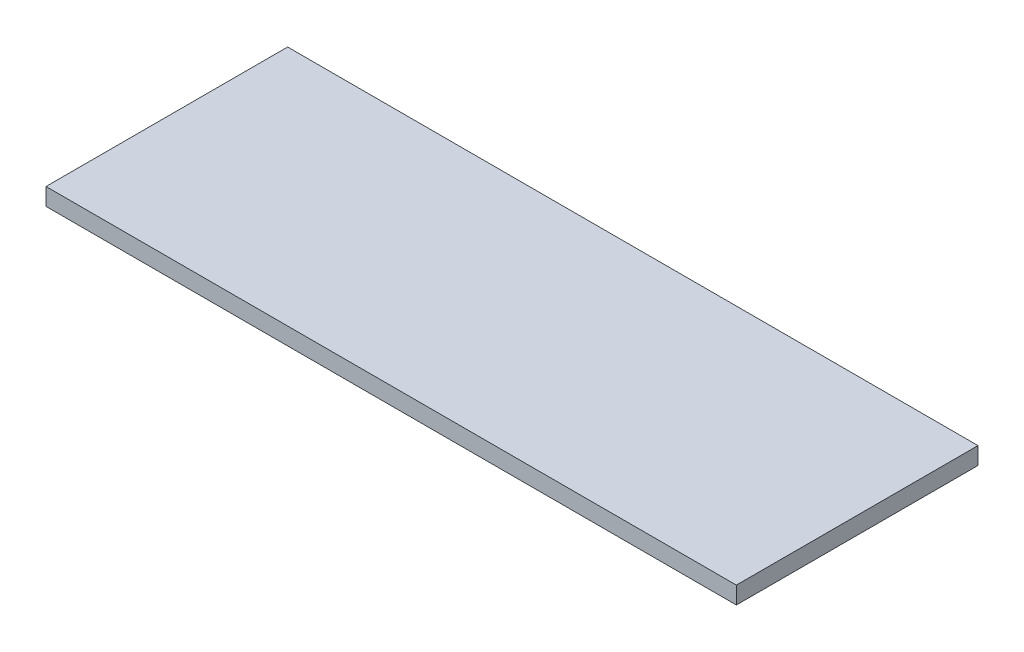
SolidWorks part; units mm, degrees
ref_plane "Front Plane" through (0, 0, 0) normal (0, 0, 1) x (1, 0, 0)
ref_plane "Top Plane" through (0, 0, 0) normal (0, 1, 0) x (1, 0, 0)
ref_plane "Right Plane" through (0, 0, 0) normal (1, 0, 0) x (0, 0, -1)
sketch "Sketch1" plane through (0, 0, 0) normal (0, 1, 0) x (1, 0, 0)
  line L1 (10, -3.5) -> (-10, -3.5)
  line L2 (10, -3.5) -> (10, 3.5)
  line L3 (10, 3.5) -> (-10, 3.5)
  line L4 (-10, -3.5) -> (-10, 3.5)
  line L5 (10, -3.5) -> (-10, 3.5) construction
  line L6 (10, 3.5) -> (-10, -3.5) construction
  point P0 (0, 0)
  dimension "D1" = 20
  dimension "D2" = 7
extrude "Boss-Extrude1" add sketch "Sketch1" along normal blind 0.5
